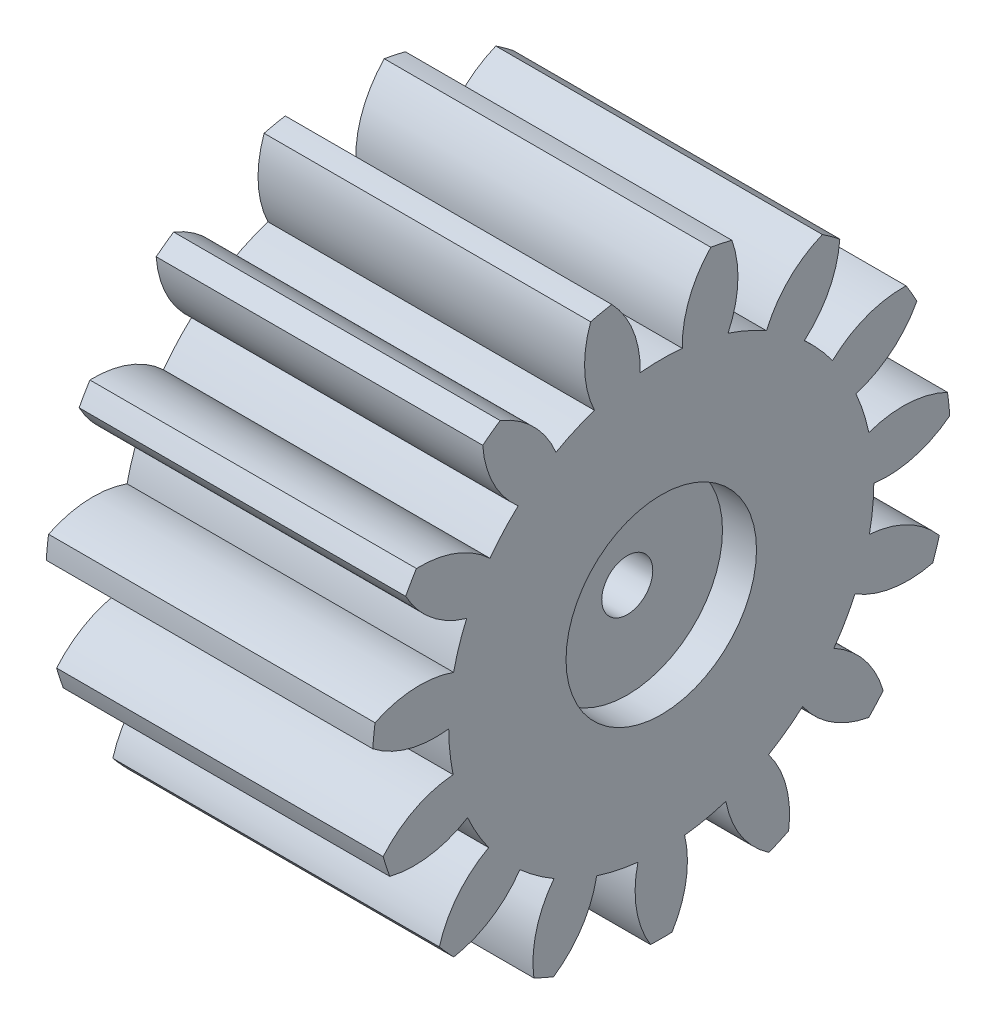
SolidWorks part; units mm, degrees
ref_plane "Plane1" through (0, 0, 0) normal (0, 0, 1) x (1, 0, 0)
ref_plane "Plane2" through (0, 0, 0) normal (0, 1, 0) x (1, 0, 0)
ref_plane "Plane3" through (0, 0, 0) normal (1, 0, 0) x (0, 0, -1)
other "Configuration Table"
sketch "HoldingSke" plane through (0, 0, 0) normal (0, 1, 0) x (1, 0, 0)
  line L0 (0, 0) -> (0.9659, -0.2588)
  line L1 (-15, 0) -> (100, 0) construction
  line L2 (0, 0) -> (-2.1039, 2.3779)
  line L3 (0, 0) -> (-11.863, 4.5341)
  line L4 (0, 0) -> (8.3417, 2.2352)
  line L5 (0, 0) -> (-46.8476, -17.4728)
  line L6 (0, 0) -> (-6.6317, -4.4744)
  line L7 (-2.1039, 2.3779) -> (8.6586, 51.2059)
  line L8 (-76.2, 54.61) -> (-76, 54.61)
  line L9 (-67.7845, 28.3722) -> (-49.3413, 33.142)
  line L10 (-76.2, 71.12) -> (104.1128, 71.12)
  line L11 (0, 0) -> (-8, 0)
  line L12 (-76.2, 101.6) -> (-76.162, 101.6)
  line L13 (24.9733, 27.94) -> (52.9518, 28.4284)
  line L14 (24.9733, 27.94) -> (24.9743, 27.94)
  line L15 (24.9733, 27.94) -> (100.4006, 29.5858)
  line L16 (-63.627, -1) -> (-12.827, -1)
  circle A0 centre (0, 0) radius 0.75
  circle A1 centre (0, 0) radius 6.249
  circle A2 centre (0, 0) radius 37.5
  circle A3 centre (0, 0) radius 0.75
  dimension "MHD" = 12.498
  dimension "Hub_dia" = 75
  dimension "Bore" = 1.5
  dimension "MBD" = 1.5
  dimension "Num_teeth" = 15
  dimension "Pitch" = 1
  dimension "Overall_len" = 50
  dimension "Show_teeth" = 15
  dimension "Thickness" = 8
  dimension "OAL" = 50.0001
  dimension "T_dim" = 0.2
  dimension "Ap" = 14.5
  dimension "H" = 19.05
  dimension "Pitch_radius" = 180.3128
  dimension "Width" = 8
  dimension "Backlash" = 0.038
  dimension "Addendum_fac" = 1
  dimension "Dedendum_fac" = 1.25
  dimension "Clearance_fac" = 0.25
  dimension "Dedendum_add" = 0.001
  dimension "Module" = 1
sketch "BasProSke" plane through (0, 0, 0) normal (0, 1, 0) x (1, 0, 0)
  line L0 (-10, 0) -> (60, 0) construction
  line L1 (0, 0) -> (0, 8.5)
  line L2 (0, 0) -> (8, 0)
  line L3 (8, 0) -> (8, 8.5)
  line L4 (8, 8.5) -> (0, 8.5)
  dimension "Thickness" = 8
  dimension "Diameter" = 17
revolve "Base-Revolve" add sketch "BasProSke" angle 360 about L0
sketch "TooCutSke" plane through (0, 0, 0) normal (1, 0, 0) x (0, 0, -1)
  line L1 (0, 0) -> (0, 107) construction
  line L2 (0, 0) -> (-0.8504, 7.4516) construction
  line L3 (0, 0) -> (-3.1044, 14.6049) construction
  line L4 (-0.8504, 7.4516) -> (-1.5522, 7.3025) construction
  arc A0 (0.6195, 6.2182) -> (-0.6195, 6.2182) centre (0, 0) ccw
  arc A1 (1.4773, 8.3964) -> (-1.4773, 8.3964) centre (0, 0) ccw
  circle A2 centre (0, 0) radius 7.5 construction
  circle A3 centre (0, 0) radius 7.2611 construction
  arc A4 (-0.6195, 6.2182) -> (-1.4773, 8.3964) centre (-3.6186, 6.2952) ccw
  arc A5 (1.4773, 8.3964) -> (0.6195, 6.2182) centre (3.6186, 6.2952) ccw
  dimension "Root_dia" = 12.498
  dimension "Overcut_dia" = 17.0508
  dimension "Pitch_dia" = 15
  dimension "Base_dia" = 14.5222
  dimension "Flank_rad" = 3
  dimension "Half_ang" = 12
  dimension "Half_CT" = 0.7175
extrude "ToothCut" cut sketch "TooCutSke" along normal through all
fillet "Breaks" [suppressed] radius 0.02
fillet "RootFillets" [suppressed] radius 0.251
pattern_circular "TeethCuts" count 15 every 24 about axis through (-10, 0, 0) along (1, 0, 0) of "ToothCut", "RootFillets", "Breaks"
sketch "HubNeaOneSke" plane through (0, 0, 0) normal (-1, 0, 0) x (0, 0, 1)
  circle A0 centre (0, 0) radius 6.249
  dimension "Diameter" = 12.498
extrude "HubNearOne" [suppressed] add sketch "HubNeaOneSke" along normal blind 42.0001
sketch "HubNeaBotSke" plane through (0, 0, 0) normal (-1, 0, 0) x (0, 0, 1)
  circle A0 centre (0, 0) radius 6.249
  dimension "Diameter" = 12.498
extrude "HubNearBoth" [suppressed] add sketch "HubNeaBotSke" along normal blind 21
ref_plane "FarPln" through (8, 0, 0) normal (1, 0, 0) x (0, 0, -1)
sketch "HubFarSke" plane through (8, 0, 0) normal (1, 0, 0) x (0, 0, -1)
  circle A0 centre (0, 0) radius 6.249
  dimension "Diameter" = 12.498
extrude "HubFar" [suppressed] add sketch "HubFarSke" along normal blind 21
sketch "BorSke" plane through (0, 0, 0) normal (1, 0, 0) x (0, 0, -1)
  circle A0 centre (0, 0) radius 0.75
  dimension "Diameter" = 1.5
extrude "Bore" cut sketch "BorSke" along normal mid plane 100.0001
sketch "KeySke" plane through (0, 0, 0) normal (1, 0, 0) x (0, 0, -1)
  line L0 (-0.3, 0) -> (-0.3, 0.95)
  line L1 (-0.3, 0.95) -> (0.3, 0.95)
  line L2 (0.3, 0.95) -> (0.3, 0)
  line L3 (0, 0) -> (0, 34) construction
  line L4 (-0.3, 0) -> (0.3, 0)
  dimension "Offset" = 0.95
  dimension "Width" = 0.6
extrude "Keyway" [suppressed] cut sketch "KeySke" along normal mid plane 100.0001
pattern_circular "Keyway2" [suppressed] count 2 every 90 about axis through (-10, 0, 0) along (1, 0, 0)
sketch "Sketch1" plane through (8, 0, 0) normal (1, 0, 0) x (0, 0, -1)
  circle A0 centre (0, 0) radius 2.8
  dimension "D1" = 5.6
extrude "Cut-Extrude2" cut sketch "Sketch1" against normal blind 1
sketch "Sketch2" plane through (0, 0, 0) normal (-1, 0, 0) x (0, 0, 1)
  circle A0 centre (0, 0) radius 0.75 construction
  circle A1 centre (0, 0) radius 0.75
  arc A60 (6.2489, -0.0338) -> (8.4807, 0.5726) centre (6.639, 2.9407) ccw
  arc A61 (8.4807, 0.5726) -> (8.4144, 1.2032) centre (0, 0) ccw
  arc A62 (8.4144, 1.2032) -> (6.1053, 1.3323) centre (7.1053, -1.4961) ccw
  arc A63 (6.1053, 1.3323) -> (5.7224, 2.5108) centre (0, 0) ccw
  arc A64 (5.7224, 2.5108) -> (7.5146, 3.9725) centre (4.8689, 5.3868) ccw
  arc A65 (7.5146, 3.9725) -> (7.1976, 4.5216) centre (0, 0) ccw
  arc A66 (7.1976, 4.5216) -> (5.0356, 3.7004) centre (7.0995, 1.5232) ccw
  arc A67 (5.0356, 3.7004) -> (4.2065, 4.6212) centre (0, 0) ccw
  arc A68 (4.2065, 4.6212) -> (5.2492, 6.6855) centre (2.257, 6.9014) ccw
  arc A69 (5.2492, 6.6855) -> (4.7362, 7.0582) centre (0, 0) ccw
  arc A70 (4.7362, 7.0582) -> (3.0952, 5.4286) centre (5.8662, 4.2792) ccw
  arc A71 (3.0952, 5.4286) -> (1.9632, 5.9326) centre (0, 0) ccw
  arc A72 (1.9632, 5.9326) -> (2.0761, 8.2426) centre (-0.7452, 7.2228) ccw
  arc A73 (2.0761, 8.2426) -> (1.4559, 8.3744) centre (0, 0) ccw
  arc A74 (1.4559, 8.3744) -> (0.6195, 6.2182) centre (3.6186, 6.2952) ccw
  arc A75 (0.6195, 6.2182) -> (-0.6195, 6.2182) centre (0, 0) ccw
  arc A76 (-0.6195, 6.2182) -> (-1.4559, 8.3744) centre (-3.6186, 6.2952) ccw
  arc A77 (-1.4559, 8.3744) -> (-2.0761, 8.2426) centre (0, 0) ccw
  arc A78 (-2.0761, 8.2426) -> (-1.9632, 5.9326) centre (0.7452, 7.2228) ccw
  arc A79 (-1.9632, 5.9326) -> (-3.0952, 5.4286) centre (0, 0) ccw
  arc A80 (-3.0952, 5.4286) -> (-4.7362, 7.0582) centre (-5.8662, 4.2792) ccw
  arc A81 (-4.7362, 7.0582) -> (-5.2492, 6.6855) centre (0, 0) ccw
  arc A82 (-5.2492, 6.6855) -> (-4.2065, 4.6212) centre (-2.257, 6.9014) ccw
  arc A83 (-4.2065, 4.6212) -> (-5.0356, 3.7004) centre (0, 0) ccw
  arc A84 (-5.0356, 3.7004) -> (-7.1976, 4.5216) centre (-7.0995, 1.5232) ccw
  arc A85 (-7.1976, 4.5216) -> (-7.5146, 3.9725) centre (0, 0) ccw
  arc A86 (-7.5146, 3.9725) -> (-5.7224, 2.5108) centre (-4.8689, 5.3868) ccw
  arc A87 (-5.7224, 2.5108) -> (-6.1053, 1.3323) centre (0, 0) ccw
  arc A88 (-6.1053, 1.3323) -> (-8.4144, 1.2032) centre (-7.1053, -1.4961) ccw
  arc A89 (-8.4144, 1.2032) -> (-8.4807, 0.5726) centre (0, 0) ccw
  arc A90 (-8.4807, 0.5726) -> (-6.2489, -0.0338) centre (-6.639, 2.9407) ccw
  arc A91 (-6.2489, -0.0338) -> (-6.1194, -1.2661) centre (0, 0) ccw
  arc A92 (-6.1194, -1.2661) -> (-8.1763, -2.3233) centre (-5.8825, -4.2568) ccw
  arc A93 (-8.1763, -2.3233) -> (-7.9804, -2.9263) centre (0, 0) ccw
  arc A94 (-7.9804, -2.9263) -> (-5.6949, -2.5726) centre (-7.2611, -0.0138) ccw
  arc A95 (-5.6949, -2.5726) -> (-5.0754, -3.6456) centre (0, 0) ccw
  arc A96 (-5.0754, -3.6456) -> (-6.5245, -5.448) centre (-3.6425, -6.2814) ccw
  arc A97 (-6.5245, -5.448) -> (-6.1002, -5.9193) centre (0, 0) ccw
  arc A98 (-6.1002, -5.9193) -> (-4.1562, -4.6665) centre (-6.6277, -2.966) ccw
  arc A99 (-4.1562, -4.6665) -> (-3.1537, -5.3948) centre (0, 0) ccw
  arc A100 (-3.1537, -5.3948) -> (-3.7445, -7.6308) centre (-0.7728, -7.2199) ccw
  arc A101 (-3.7445, -7.6308) -> (-3.1652, -7.8887) centre (0, 0) ccw
  arc A102 (-3.1652, -7.8887) -> (-1.8988, -5.9535) centre (-4.8483, -5.4053) ccw
  arc A103 (-1.8988, -5.9535) -> (-0.6868, -6.2111) centre (0, 0) ccw
  arc A104 (-0.6868, -6.2111) -> (-0.317, -8.4941) centre (2.2306, -6.91) ccw
  arc A105 (-0.317, -8.4941) -> (0.317, -8.4941) centre (0, 0) ccw
  arc A106 (0.317, -8.4941) -> (0.6868, -6.2111) centre (-2.2306, -6.91) ccw
  arc A107 (0.6868, -6.2111) -> (1.8988, -5.9535) centre (0, 0) ccw
  arc A108 (1.8988, -5.9535) -> (3.1652, -7.8887) centre (4.8483, -5.4053) ccw
  arc A109 (3.1652, -7.8887) -> (3.7445, -7.6308) centre (0, 0) ccw
  arc A110 (3.7445, -7.6308) -> (3.1537, -5.3948) centre (0.7728, -7.2199) ccw
  arc A111 (3.1537, -5.3948) -> (4.1562, -4.6665) centre (0, 0) ccw
  arc A112 (4.1562, -4.6665) -> (6.1002, -5.9193) centre (6.6277, -2.966) ccw
  arc A113 (6.1002, -5.9193) -> (6.5245, -5.448) centre (0, 0) ccw
  arc A114 (6.5245, -5.448) -> (5.0754, -3.6456) centre (3.6425, -6.2814) ccw
  arc A115 (5.0754, -3.6456) -> (5.6949, -2.5726) centre (0, 0) ccw
  arc A116 (5.6949, -2.5726) -> (7.9804, -2.9263) centre (7.2611, -0.0138) ccw
  arc A117 (7.9804, -2.9263) -> (8.1763, -2.3233) centre (0, 0) ccw
  arc A118 (8.1763, -2.3233) -> (6.1194, -1.2661) centre (5.8825, -4.2568) ccw
  arc A119 (6.1194, -1.2661) -> (6.2489, -0.0338) centre (0, 0) ccw
  arc A120 (6.2489, -0.0338) -> (8.4807, 0.5726) centre (6.639, 2.9407) ccw
  arc A121 (8.4807, 0.5726) -> (8.4144, 1.2032) centre (0, 0) ccw
  arc A122 (8.4144, 1.2032) -> (6.1053, 1.3323) centre (7.1053, -1.4961) ccw
  arc A123 (6.1053, 1.3323) -> (5.7224, 2.5108) centre (0, 0) ccw
  arc A124 (5.7224, 2.5108) -> (7.5146, 3.9725) centre (4.8689, 5.3868) ccw
  arc A125 (7.5146, 3.9725) -> (7.1976, 4.5216) centre (0, 0) ccw
  arc A126 (7.1976, 4.5216) -> (5.0356, 3.7004) centre (7.0995, 1.5232) ccw
  arc A127 (5.0356, 3.7004) -> (4.2065, 4.6212) centre (0, 0) ccw
  arc A128 (4.2065, 4.6212) -> (5.2492, 6.6855) centre (2.257, 6.9014) ccw
  arc A129 (5.2492, 6.6855) -> (4.7362, 7.0582) centre (0, 0) ccw
  arc A130 (4.7362, 7.0582) -> (3.0952, 5.4286) centre (5.8662, 4.2792) ccw
  arc A131 (3.0952, 5.4286) -> (1.9632, 5.9326) centre (0, 0) ccw
  arc A132 (1.9632, 5.9326) -> (2.0761, 8.2426) centre (-0.7452, 7.2228) ccw
  arc A133 (2.0761, 8.2426) -> (1.4559, 8.3744) centre (0, 0) ccw
  arc A134 (1.4559, 8.3744) -> (0.6195, 6.2182) centre (3.6186, 6.2952) ccw
  arc A135 (0.6195, 6.2182) -> (-0.6195, 6.2182) centre (0, 0) ccw
  arc A136 (-0.6195, 6.2182) -> (-1.4559, 8.3744) centre (-3.6186, 6.2952) ccw
  arc A137 (-1.4559, 8.3744) -> (-2.0761, 8.2426) centre (0, 0) ccw
  arc A138 (-2.0761, 8.2426) -> (-1.9632, 5.9326) centre (0.7452, 7.2228) ccw
  arc A139 (-1.9632, 5.9326) -> (-3.0952, 5.4286) centre (0, 0) ccw
  arc A140 (-3.0952, 5.4286) -> (-4.7362, 7.0582) centre (-5.8662, 4.2792) ccw
  arc A141 (-4.7362, 7.0582) -> (-5.2492, 6.6855) centre (0, 0) ccw
  arc A142 (-5.2492, 6.6855) -> (-4.2065, 4.6212) centre (-2.257, 6.9014) ccw
  arc A143 (-4.2065, 4.6212) -> (-5.0356, 3.7004) centre (0, 0) ccw
  arc A144 (-5.0356, 3.7004) -> (-7.1976, 4.5216) centre (-7.0995, 1.5232) ccw
  arc A145 (-7.1976, 4.5216) -> (-7.5146, 3.9725) centre (0, 0) ccw
  arc A146 (-7.5146, 3.9725) -> (-5.7224, 2.5108) centre (-4.8689, 5.3868) ccw
  arc A147 (-5.7224, 2.5108) -> (-6.1053, 1.3323) centre (0, 0) ccw
  arc A148 (-6.1053, 1.3323) -> (-8.4144, 1.2032) centre (-7.1053, -1.4961) ccw
  arc A149 (-8.4144, 1.2032) -> (-8.4807, 0.5726) centre (0, 0) ccw
  arc A150 (-8.4807, 0.5726) -> (-6.2489, -0.0338) centre (-6.639, 2.9407) ccw
  arc A151 (-6.2489, -0.0338) -> (-6.1194, -1.2661) centre (0, 0) ccw
  arc A152 (-6.1194, -1.2661) -> (-8.1763, -2.3233) centre (-5.8825, -4.2568) ccw
  arc A153 (-8.1763, -2.3233) -> (-7.9804, -2.9263) centre (0, 0) ccw
  arc A154 (-7.9804, -2.9263) -> (-5.6949, -2.5726) centre (-7.2611, -0.0138) ccw
  arc A155 (-5.6949, -2.5726) -> (-5.0754, -3.6456) centre (0, 0) ccw
  arc A156 (-5.0754, -3.6456) -> (-6.5245, -5.448) centre (-3.6425, -6.2814) ccw
  arc A157 (-6.5245, -5.448) -> (-6.1002, -5.9193) centre (0, 0) ccw
  arc A158 (-6.1002, -5.9193) -> (-4.1562, -4.6665) centre (-6.6277, -2.966) ccw
  arc A159 (-4.1562, -4.6665) -> (-3.1537, -5.3948) centre (0, 0) ccw
  arc A160 (-3.1537, -5.3948) -> (-3.7445, -7.6308) centre (-0.7728, -7.2199) ccw
  arc A161 (-3.7445, -7.6308) -> (-3.1652, -7.8887) centre (0, 0) ccw
  arc A162 (-3.1652, -7.8887) -> (-1.8988, -5.9535) centre (-4.8483, -5.4053) ccw
  arc A163 (-1.8988, -5.9535) -> (-0.6868, -6.2111) centre (0, 0) ccw
  arc A164 (-0.6868, -6.2111) -> (-0.317, -8.4941) centre (2.2306, -6.91) ccw
  arc A165 (-0.317, -8.4941) -> (0.317, -8.4941) centre (0, 0) ccw
  arc A166 (0.317, -8.4941) -> (0.6868, -6.2111) centre (-2.2306, -6.91) ccw
  arc A167 (0.6868, -6.2111) -> (1.8988, -5.9535) centre (0, 0) ccw
  arc A168 (1.8988, -5.9535) -> (3.1652, -7.8887) centre (4.8483, -5.4053) ccw
  arc A169 (3.1652, -7.8887) -> (3.7445, -7.6308) centre (0, 0) ccw
  arc A170 (3.7445, -7.6308) -> (3.1537, -5.3948) centre (0.7728, -7.2199) ccw
  arc A171 (3.1537, -5.3948) -> (4.1562, -4.6665) centre (0, 0) ccw
  arc A172 (4.1562, -4.6665) -> (6.1002, -5.9193) centre (6.6277, -2.966) ccw
  arc A173 (6.1002, -5.9193) -> (6.5245, -5.448) centre (0, 0) ccw
  arc A174 (6.5245, -5.448) -> (5.0754, -3.6456) centre (3.6425, -6.2814) ccw
  arc A175 (5.0754, -3.6456) -> (5.6949, -2.5726) centre (0, 0) ccw
  arc A176 (5.6949, -2.5726) -> (7.9804, -2.9263) centre (7.2611, -0.0138) ccw
  arc A177 (7.9804, -2.9263) -> (8.1763, -2.3233) centre (0, 0) ccw
  arc A178 (8.1763, -2.3233) -> (6.1194, -1.2661) centre (5.8825, -4.2568) ccw
  arc A179 (6.1194, -1.2661) -> (6.2489, -0.0338) centre (0, 0) ccw
  dimension "D1" = 0
extrude "Boss-Extrude2" add sketch "Sketch2" along normal blind 1.6
equation "' \"Module@HoldingSke\" = 6.35"
equation "' \"Num_teeth@HoldingSke\" = 12"
equation "' \"Ap@HoldingSke\" =  20"
equation "' \"Ap@HoldingSke\" = 20"
equation "' \"Width@HoldingSke\" = 0.5 * 25.4"
equation "' \"Hub_dia@HoldingSke\"= 1 * 25.4"
equation "' \"Hub_dia@HoldingSke\" = 1 * 25.4"
equation "' \"Overall_len@HoldingSke\" = 1.0 * 25.4"
equation "' \"Bore@HoldingSke\" = 0.75 * 25.4"
equation "' \"T_dim@HoldingSke\" = 0.1 * 25.4"
equation "' \"Width@KeySke\" = 0.25 * 25.4"
equation "' \"Show_teeth@HoldingSke\" = 13"
equation "' \"Backlash@HoldingSke\" = 0.009 * 25.4"
equation "' \"Addendum_fac@HoldingSke\" = 1.0"
equation "' \"Dedendum_fac@HoldingSke\" = 1.25"
equation "' \"Dedendum_add@HoldingSke\" = 0.00005 * 25.4"
equation "' \"Clearance_fac@HoldingSke\" = 0.25"
equation "\"Pitch@HoldingSke\" = 1 / \"Module@HoldingSke\""
equation "\"Overcut_dia@TooCutSke\" = (\"Num_teeth@HoldingSke\" + 2 * \"Addendum_fac@HoldingSke\") / \"Pitch@HoldingSke\" + 0.002 * 25.4"
equation "\"Pitch_dia@TooCutSke\" = \"Num_teeth@HoldingSke\" / \"Pitch@HoldingSke\""
equation "\"Base_dia@TooCutSke\" = \"Num_teeth@HoldingSke\" / \"Pitch@HoldingSke\" * cos((\"Ap@HoldingSke\"  * 3.14159265 / 180))"
equation "\"Root_dia@TooCutSke\" = (\"Num_teeth@HoldingSke\" + 2) / \"Pitch@HoldingSke\" - 2 * (\"Addendum_fac@HoldingSke\" + \"Dedendum_fac@HoldingSke\") / \"Pitch@HoldingSke\" - \"Dedendum_add@HoldingSke\" * 2"
equation "\"Half_ang@TooCutSke\" = 180 / \"Num_teeth@HoldingSke\""
equation "\"Half_CT@TooCutSke\" = \"Num_teeth@HoldingSke\" / \"Pitch@HoldingSke\" * sin((3.14159265 / 2 / \"Num_teeth@HoldingSke\")) / 2 - 7 * \"Backlash@HoldingSke\" / 4"
equation "\"Flank_rad@TooCutSke\" = \"Num_teeth@HoldingSke\" / \"Pitch@HoldingSke\" / 5"
equation "\"Radius@RootFillets\" = \"Clearance_fac@HoldingSke\" / \"Pitch@HoldingSke\" + \"Dedendum_add@HoldingSke\""
equation "\"Break_rad@Breaks\" = 0.02 / \"Pitch@HoldingSke\""
equation "\"Thickness@HoldingSke\" = \"Width@HoldingSke\""
equation "\"OAL@HoldingSke\" = \"Thickness@HoldingSke\""
equation "\"MHD@HoldingSke\" = (\"Num_teeth@HoldingSke\" + 2) / \"Pitch@HoldingSke\" - 2 * (\"Addendum_fac@HoldingSke\" + \"Dedendum_fac@HoldingSke\")  / \"Pitch@HoldingSke\" - \"Dedendum_add@HoldingSke\" * 2"
equation "\"MBD@HoldingSke\" = (\"Num_teeth@HoldingSke\" + 2) / \"Pitch@HoldingSke\" - 2 * (\"Addendum_fac@HoldingSke\" + \"Dedendum_fac@HoldingSke\")  / \"Pitch@HoldingSke\" - \"Dedendum_add@HoldingSke\" * 2 - 0.002 * 25.4"
equation "\"MHD@HoldingSke\" = ((sgn( \"MHD@HoldingSke\" - \"Hub_dia@HoldingSke\" )-1)*( \"MHD@HoldingSke\" - \"Hub_dia@HoldingSke\" ))/-2+ \"Hub_dia@HoldingSke\""
equation "\"MBD@HoldingSke\" = ((sgn( \"MBD@HoldingSke\" - \"Bore@HoldingSke\" )-1)*( \"MBD@HoldingSke\" - \"Bore@HoldingSke\" ))/-2+ \"Bore@HoldingSke\""
equation "\"OAL@HoldingSke\" = ((sgn( \"OAL@HoldingSke\" - \"Overall_len@HoldingSke\" )+1)*( \"OAL@HoldingSke\" - \"Overall_len@HoldingSke\" ))/2 + \"Overall_len@HoldingSke\" + 0.000002 * 25.4"
equation "\"Num_teeth@TeethCuts\" = int( \"Show_teeth@HoldingSke\" ) + 1"
equation "\"Num_teeth@TeethCuts\" = ((sgn( \"Num_teeth@TeethCuts\" - \"Num_teeth@HoldingSke\" )-1)*( \"Num_teeth@TeethCuts\" - \"Num_teeth@HoldingSke\" ))/-2+ \"Num_teeth@HoldingSke\""
equation "\"Num_teeth@TeethCuts\" = ((sgn( \"Num_teeth@TeethCuts\" - 2.0)+1)*( \"Num_teeth@TeethCuts\" - 2.0))/2 +2.0"
equation "\"Angle@TeethCuts\" = 360.0 / \"Num_teeth@HoldingSke\""
equation "\"Diameter@BasProSke\" = (\"Num_teeth@HoldingSke\" + 2 * \"Addendum_fac@HoldingSke\") / \"Pitch@HoldingSke\""
equation "\"Thickness@BasProSke\"  = \"Thickness@HoldingSke\""
equation "' \"Fillet_rad@BasProSke\" =  \"Thickness@HoldingSke\" * 0.05"
equation "' \"Fillet_rad@BasProSke\" = \"Thickness@HoldingSke\" * 0.05"
equation "\"MHD@HoldingSke\" = ((sgn( \"MHD@HoldingSke\" - \"Root_dia@TooCutSke\" )-1)*( \"MHD@HoldingSke\" - \"Root_dia@TooCutSke\" ))/-2+ \"Root_dia@TooCutSke\""
equation "\"Diameter@HubNeaOneSke\" = \"MHD@HoldingSke\""
equation "\"Length@HubNearOne\" = \"OAL@HoldingSke\" - \"Thickness@BasProSke\""
equation "\"Diameter@HubNeaBotSke\" = \"MHD@HoldingSke\""
equation "\"Length@HubNearBoth\" = ( \"OAL@HoldingSke\" - \"Thickness@BasProSke\" ) / 2.0"
equation "\"Thickness@FarPln\" = \"Thickness@BasProSke\""
equation "\"Diameter@HubFarSke\" = \"MHD@HoldingSke\""
equation "\"Length@HubFar\" = ( \"OAL@HoldingSke\" - \"Thickness@BasProSke\" ) / 2.0"
equation "\"Diameter@BorSke\" = \"MBD@HoldingSke\""
equation "\"D1@Bore\" = \"OAL@HoldingSke\" * 2.0"
equation "\"D1@Keyway\" = \"OAL@HoldingSke\" * 2.0"
equation "\"Offset@KeySke\" = \"T_dim@HoldingSke\" + \"MBD@HoldingSke\" / 2.0"
